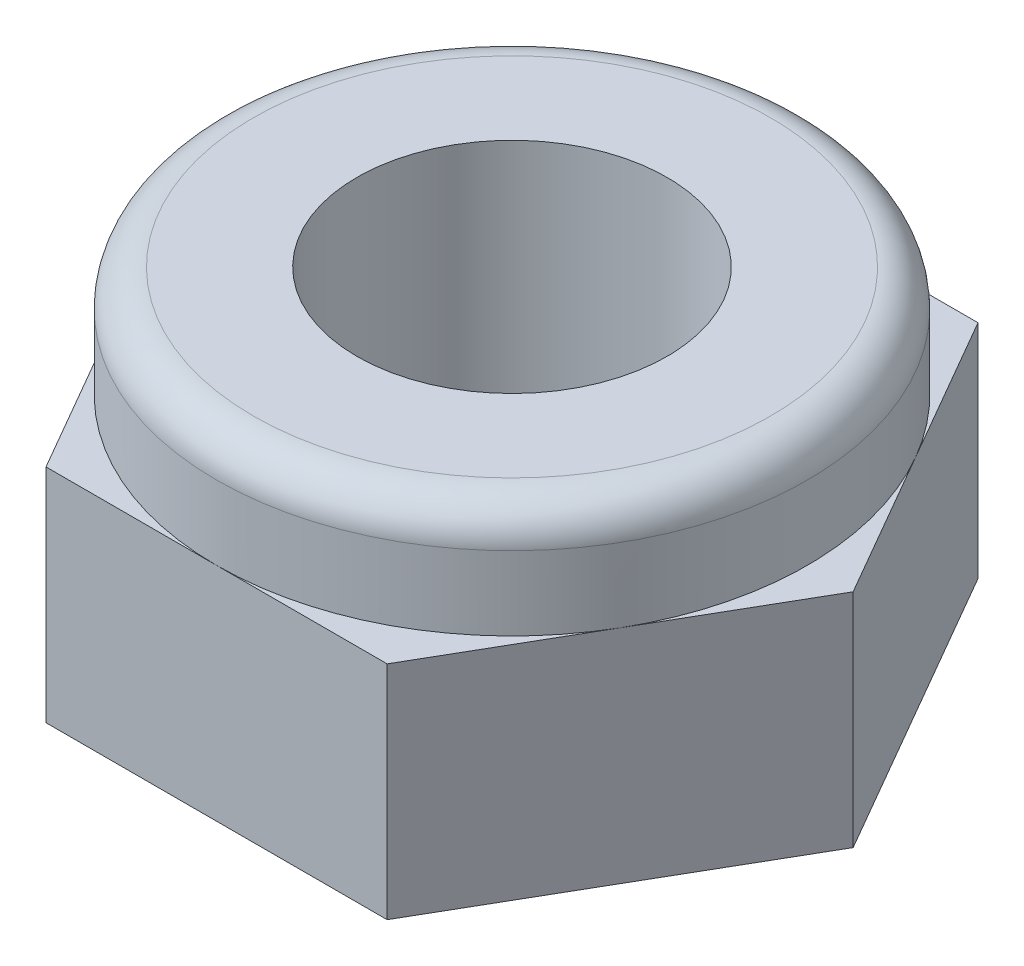
SolidWorks part; units mm, degrees
ref_plane "Front Plane" through (0, 0, 0) normal (0, 0, 1) x (1, 0, 0)
ref_plane "Top Plane" through (0, 0, 0) normal (0, 1, 0) x (1, 0, 0)
ref_plane "Right Plane" through (0, 0, 0) normal (1, 0, 0) x (0, 0, -1)
sketch "Sketch1" plane through (0, 0, 0) normal (0, 1, 0) x (1, 0, 0)
  line L0 (4.6188, 0) -> (0, 0) construction
  line L1 (4.6188, 0) -> (2.3094, 4)
  line L2 (2.3094, 4) -> (-2.3094, 4)
  line L3 (-2.3094, 4) -> (-4.6188, 0)
  line L4 (-4.6188, 0) -> (-2.3094, -4)
  line L5 (-2.3094, -4) -> (2.3094, -4)
  line L6 (2.3094, -4) -> (4.6188, 0)
  circle A0 centre (0, 0) radius 2.5 construction
  circle A1 centre (0, 0) radius 4 construction
  dimension "D1" = 8
  dimension "D2" = 5
extrude "Boss-Extrude1" add sketch "Sketch1" along normal blind 3
sketch "Sketch2" plane through (0, 3, 0) normal (0, 1, 0) x (1, 0, 0)
  circle A0 centre (0, 0) radius 4
  circle A1 centre (0, 0) radius 4 construction
extrude "Boss-Extrude2" add sketch "Sketch2" along normal blind 1.5
hole_wizard "M5x0.8 Tapped Hole1" positions "Sketch3" profile "Sketch4" tap size "M5x0.8" standard "ANSI Metric" end condition up to next
sketch "Sketch3" plane through (0, 4.5, 0) normal (0, 1, 0) x (1, 0, 0)
  point P0 (0, 0)
sketch "Sketch4" plane through (0, 4.5, 0) normal (1, 0, 0) x (0, 0, 1)
  line L0 (0, 0) -> (0, 4.5)
  line L1 (0, 4.5) -> (2.1, 4.5)
  line L2 (2.1, 4.5) -> (2.1, 0)
  line L5 (2.1, 0) -> (0, 0)
  line L11 (0, -6.35) -> (0, 107.95) construction
  dimension "Thru Tap Drill Dia." = 4.2
  dimension "Thru Tap Drill Depth" = 4.5
cosmetic thread "Hole Thread1" parameters "D2"=5
fillet "Fillet1" radius 0.5 1 edges at (0, 4.5, 4)
